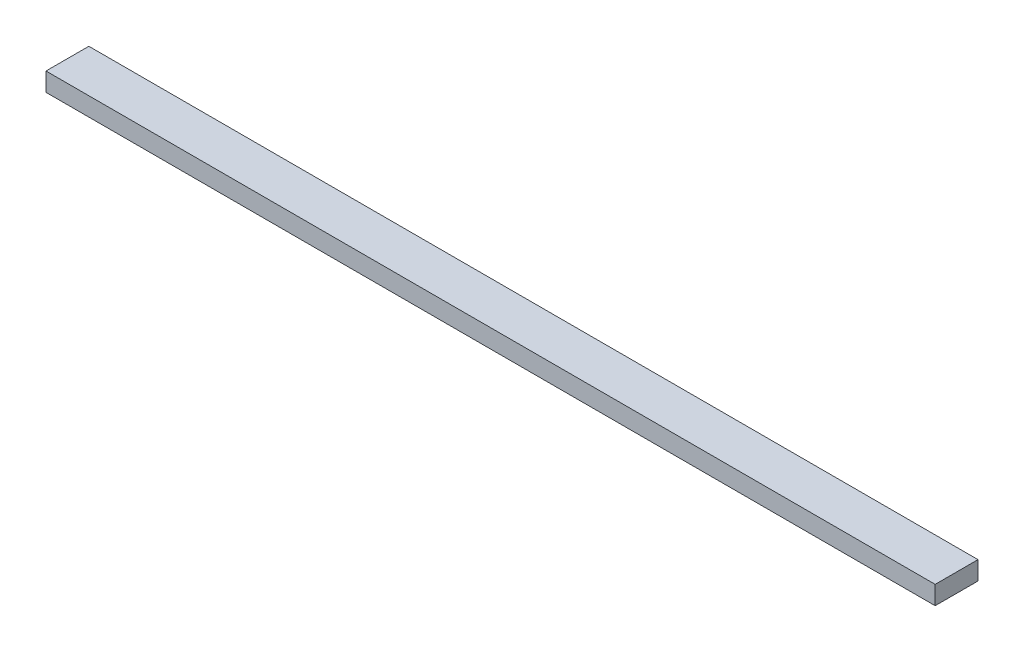
SolidWorks part; units mm, degrees
material "Pine"
ref_plane "Front Plane" through (0, 0, 0) normal (0, 0, 1) x (1, 0, 0)
ref_plane "Top Plane" through (0, 0, 0) normal (0, 1, 0) x (1, 0, 0)
ref_plane "Right Plane" through (0, 0, 0) normal (1, 0, 0) x (0, 0, -1)
sketch "Sketch1" plane through (0, 0, 0) normal (1, 0, 0) x (0, 0, -1)
  line L1 (44.0531, -19.05) -> (-44.0531, -19.05)
  line L2 (44.0531, -19.05) -> (44.0531, 19.05)
  line L3 (44.0531, 19.05) -> (-44.0531, 19.05)
  line L4 (-44.0531, -19.05) -> (-44.0531, 19.05)
  line L5 (44.0531, -19.05) -> (-44.0531, 19.05) construction
  line L6 (44.0531, 19.05) -> (-44.0531, -19.05) construction
  point P0 (0, 0)
  dimension "D1" = 88.1063
  dimension "D2" = 38.1
extrude "Boss-Extrude1" add sketch "Sketch1" along normal up to surface (1828.8 mm away)
